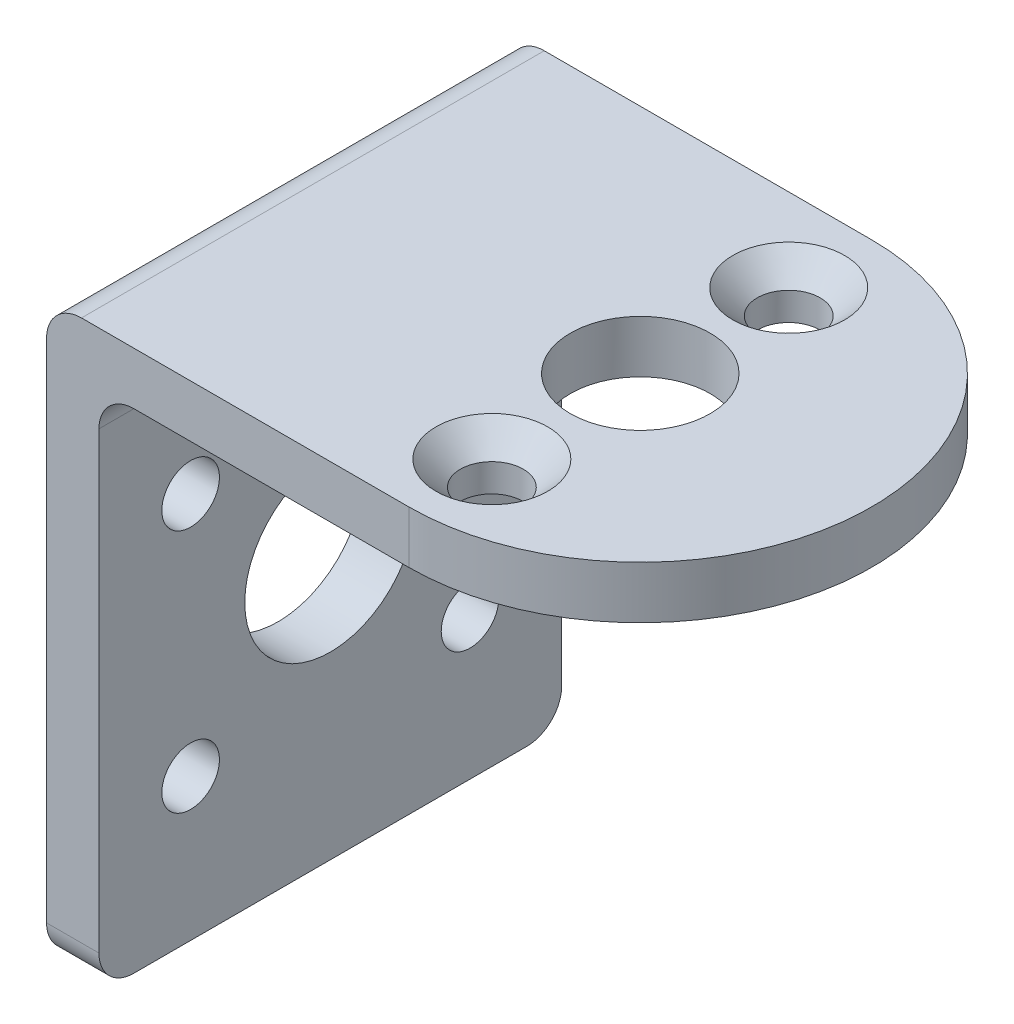
SolidWorks part; units mm, degrees
material "普通碳钢"
ref_plane "前视" through (0, 0, 0) normal (0, 0, 1) x (1, 0, 0)
ref_plane "上视" through (0, 0, 0) normal (0, 1, 0) x (1, 0, 0)
ref_plane "右视" through (0, 0, 0) normal (1, 0, 0) x (0, 0, -1)
sketch "草图1" plane through (0, 0, 0) normal (0, 0, 1) x (1, 0, 0)
  line L0 (0, -33) -> (0, -2)
  line L1 (2, 0) -> (50, 0)
  line L2 (3, -33) -> (3, -5)
  line L3 (5, -3) -> (50, -3)
  line L4 (0, -33) -> (3, -33)
  line L5 (50, 0) -> (50, -3)
  line L6 (3, -33) -> (3, -3) construction
  line L7 (3, -3) -> (50, -3) construction
  line L8 (0, -33) -> (0, 0) construction
  line L9 (0, 0) -> (50, 0) construction
  arc A0 (3, -5) -> (5, -3) centre (5, -5) cw
  arc A1 (0, -2) -> (2, 0) centre (2, -2) cw
  point P13 (0, 0)
  dimension "D4" = 2
  dimension "D2" = 33
  dimension "D3" = 50
  dimension "D1" = 3
extrude "凸台-拉伸1" add sketch "草图1" along normal mid plane 26.5 contours L3 L5 L1 A1 L0 L4 L2 A0
sketch "草图3" plane through (0, -3, 0) normal (0, -1, 0) x (1, 0, 0)
  line L0 (20.75, 13.25) -> (20.75, -13.25) construction
  line L1 (5, 13.25) -> (50, 13.25) construction
  line L2 (5, -13.25) -> (50, -13.25) construction
  line L3 (20.75, 13.25) -> (50, 13.25)
  line L4 (20.75, -13.25) -> (50, -13.25)
  line L5 (0, 0) -> (34, 0) construction
  line L6 (50, -13.25) -> (50, 13.25)
  line L10 (50, 0) -> (0, 0) construction
  arc A0 (20.75, 13.25) -> (20.75, -13.25) centre (20.75, 0) cw
  dimension "D1" = 34
extrude "切除-拉伸2" cut sketch "草图3" against normal blind 40
sketch "草图5" plane through (0, 0, 0) normal (-1, 0, 0) x (0, 0, 1)
  line L0 (0, 0) -> (0, -33) construction
  line L1 (13.25, -33) -> (-13.25, -33) construction
  circle A0 centre (8, -10.85) radius 1.65
  circle A1 centre (8, -24.85) radius 1.65
  circle A2 centre (-8, -24.85) radius 1.65
  circle A3 centre (-8, -10.85) radius 1.65
  circle A4 centre (0, -17.8) radius 4.9
  dimension "D1" = 3.3
  dimension "D2" = 14
  dimension "D3" = 16
  dimension "D4" = 8.15
  dimension "D5" = 16
  dimension "D6" = 9.8
  dimension "D7" = 15.2
extrude "切除-拉伸4" cut sketch "草图5" against normal blind 40
fillet "圆角1" radius 2 2 edges at (1.5, -33, -13.25) (1.5, -33, 13.25)
sketch "草图7" plane through (0, 0, 0) normal (0, 1, 0) x (1, 0, 0)
  line L0 (34, 0) -> (0, 0) construction
  arc A0 (20.75, -13.25) -> (20.75, 13.25) centre (20.75, 0) ccw construction
  circle A1 centre (20.75, 0) radius 4
  dimension "D1" = 8
  dimension "D2" = 20.75
extrude "切除-拉伸5" cut sketch "草图7" against normal blind 10
sketch "草图10" plane through (0, 0, 0) normal (0, 1, 0) x (1, 0, 0)
  line L0 (20.75, 13.25) -> (20.75, -13.25) construction
  line L1 (20.75, 8.5) -> (20.75, -8.5) construction
  line L2 (20.75, 0) -> (0, 0) construction
  dimension "D1" = 17
hole_wizard "打孔尺寸开槽半沉头螺钉的类型1" positions "草图9" profile "草图8" countersink size "M3" standard "GB"
sketch "草图9" plane through (0, 0, 0) normal (0, 1, 0) x (1, 0, 0)
  point P0 (20.75, -8.5)
sketch "草图8" plane through (20.75, 0, 8.5) normal (1, 0, 0) x (0, 0, 1)
  line L0 (0, 0) -> (0, 9.0815)
  line L1 (0, 9.0815) -> (1.8, 8)
  line L2 (1.8, 8) -> (1.8, 1.4)
  line L3 (1.8, 1.4) -> (3.2, 0)
  line L5 (3.2, 0) -> (0, 0)
  line L6 (-1.8, 1.4) -> (-3.2, 0) construction
  line L10 (0, 9.0815) -> (-1.8, 8) construction
  line L11 (0, -6.35) -> (0, 107.95) construction
  dimension "孔直径" = 3.6
  dimension "孔深度" = 8
  dimension "近端锥形沉头孔直径" = 6.4
  dimension "近端锥形沉头孔角度" = 90
  dimension "导头角度" = 118
hole_wizard "打孔尺寸开槽半沉头螺钉的类型2" positions "草图13" profile "草图14" countersink size "M3" standard "GB"
sketch "草图13" plane through (0, 0, 0) normal (0, 1, 0) x (1, 0, 0)
  point P0 (20.75, 8.5)
sketch "草图14" plane through (20.75, 0, -8.5) normal (1, 0, 0) x (0, 0, 1)
  line L0 (0, 0) -> (0, 9.0815)
  line L1 (0, 9.0815) -> (1.8, 8)
  line L2 (1.8, 8) -> (1.8, 1.4)
  line L3 (1.8, 1.4) -> (3.2, 0)
  line L5 (3.2, 0) -> (0, 0)
  line L6 (-1.8, 1.4) -> (-3.2, 0) construction
  line L10 (0, 9.0815) -> (-1.8, 8) construction
  line L11 (0, -6.35) -> (0, 107.95) construction
  dimension "孔直径" = 3.6
  dimension "孔深度" = 8
  dimension "近端锥形沉头孔直径" = 6.4
  dimension "近端锥形沉头孔角度" = 90
  dimension "导头角度" = 118
